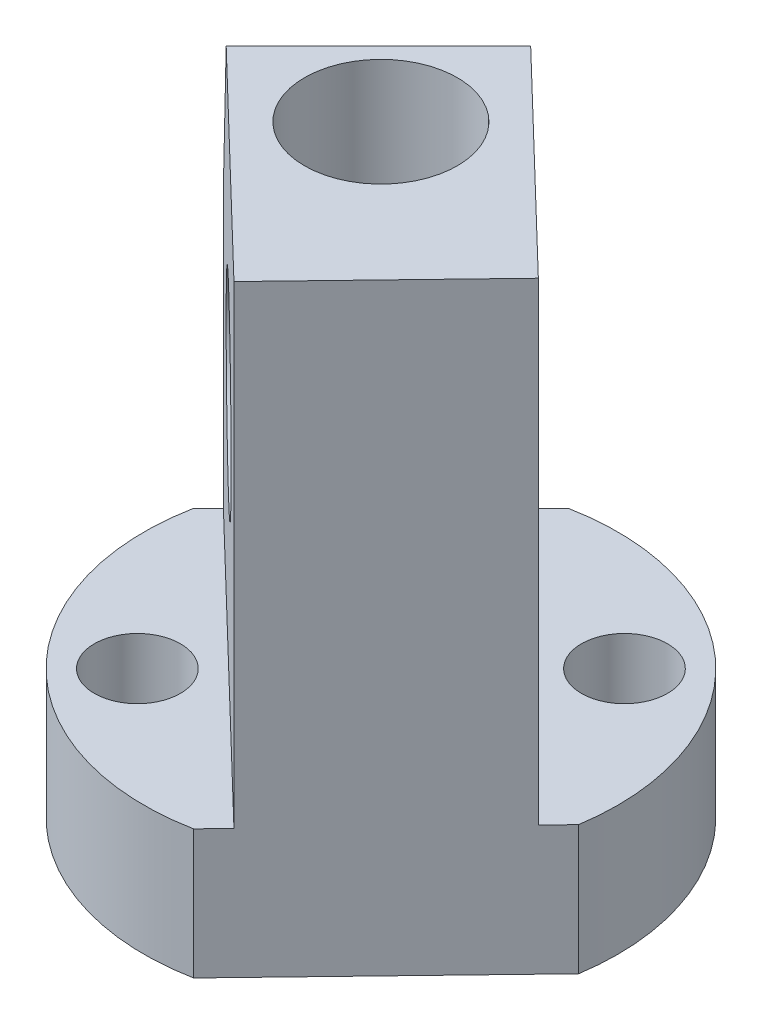
SolidWorks part; units mm, degrees
ref_plane "Plan de face" through (0, 0, 0) normal (0, 0, 1) x (1, 0, 0)
ref_plane "Plan de dessus" through (0, 0, 0) normal (0, 1, 0) x (1, 0, 0)
ref_plane "Plan de droite" through (0, 0, 0) normal (1, 0, 0) x (0, 0, -1)
ref_plane "Plan1" through (0, 0, 0) normal (0, 0, -1) x (-1, 0, 0)
sketch "Esquisse1" plane through (0, 0, 0) normal (0, 0, -1) x (-1, 0, 0)
  line L0 (-11, 0) -> (0, 0)
  line L1 (0, 0) -> (0, 6)
  line L2 (0, 6) -> (-11, 6)
  line L3 (-11, 6) -> (-11, 0)
  line L4 (0, 0) -> (0, 6) construction
revolve "Révolution1" add sketch "Esquisse1" angle 360 about L4
sketch "Esquisse2" plane through (0, 6, 0) normal (0, 1, 0) x (-1, 0, 0)
  line L0 (-9.9516, 2.6394) -> (-3.0164, 9.8438)
  line L1 (-3.0164, 9.8438) -> (10.0888, -2.7715)
  line L2 (10.0888, -2.7715) -> (3.0164, -9.8438)
  line L3 (3.0164, -9.8438) -> (-9.9516, 2.6394)
extrude "Boss.-Extru.1" add sketch "Esquisse2" along normal blind 22
hole_wizard "Diamètre du perçage Ø7.1 (7.1)1" positions "Esquisse4" profile "Esquisse3" hole size "Ø7.1" standard "Ansi Metric"
sketch "Esquisse4" plane through (0, 28, 0) normal (0, 1, 0) x (1, 0, 0)
  point P0 (0, 0)
sketch "Esquisse3" plane through (0, 28, 0) normal (1, 0, 0) x (0, 0, 1)
  line L0 (0, 0) -> (0, 6)
  line L1 (0, 6) -> (3.55, 6)
  line L2 (3.55, 6) -> (3.55, 0)
  line L5 (3.55, 0) -> (0, 0)
  line L10 (0, 6) -> (-3.55, 6) construction
  line L11 (0, -6.35) -> (0, 107.95) construction
  dimension "Diamètre du perçage" = 7.1
  dimension "Profondeur du perçage" = 6
  dimension "Angle de pointe" = 180
hole_wizard "Diamètre du perçage Ø8.5 (8.5)1" positions "Esquisse6" profile "Esquisse5" hole size "Ø8.5" standard "Ansi Metric" end condition through all
sketch "Esquisse6" plane through (-3.4676, 0, 3.6022) normal (-0.6935, 0, 0.7204) x (0.7204, 0, 0.6935)
  point P0 (-0.1905, 17)
sketch "Esquisse5" plane through (-3.6048, 17, 3.4701) normal (0, 1, 0) x (0.7204, 0, 0.6935)
  line L0 (0, 0) -> (0, 20.5535)
  line L1 (0, 20.5535) -> (4.25, 20.5535)
  line L2 (4.25, 20.5535) -> (4.25, 0)
  line L5 (4.25, 0) -> (0, 0)
  line L11 (0, -6.35) -> (0, 107.95) construction
  dimension "Diamètre du perçage jusqu'au prochain" = 8.5
  dimension "Profondeur du perçage jusqu'au prochain" = 20.5535
hole_wizard "Chambrage pour vis à tête hexagonale M21" positions "Esquisse8" profile "Esquisse7" counterbore size "M2" standard "Ansi Metric"
sketch "Esquisse8" plane through (0, 6, 0) normal (0, 1, 0) x (1, 0, 0)
  point P0 (5.6569, 5.6569)
  point P1 (-5.6569, -5.6569)
sketch "Esquisse7" plane through (5.6569, 6, -5.6569) normal (1, 0, 0) x (0, 0, 1)
  line L0 (0, 0) -> (0, 6)
  line L1 (0, 6) -> (1.25, 6)
  line L3 (1.25, 6) -> (1.25, 4.5)
  line L4 (1.25, 4.5) -> (2, 4.5)
  line L5 (2, 4.5) -> (2, 0)
  line L7 (2, 0) -> (0, 0)
  line L11 (0, -6.35) -> (0, 107.95) construction
  dimension "Diamètre du perçage jusqu'au prochain" = 2.5
  dimension "Profondeur du perçage jusqu'au prochain" = 6
  dimension "Diamètre du chambrage" = 4
  dimension "Profondeur du chambrage" = 4.5
hole_wizard "Diamètre du perçage Ø8.0 (8)1" positions "Esquisse10" profile "Esquisse9" hole size "Ø8.0" standard "Ansi Metric"
sketch "Esquisse10" plane through (0, 0, 0) normal (0, -1, 0) x (-1, 0, 0)
  point P0 (0, 0)
sketch "Esquisse9" plane through (0, 0, 0) normal (1, 0, 0) x (0, 0, -1)
  line L0 (0, 0) -> (0, 6)
  line L1 (0, 6) -> (4, 2)
  line L2 (4, 2) -> (4, 0)
  line L5 (4, 0) -> (0, 0)
  line L10 (0, 6) -> (-4, 2) construction
  line L11 (0, -6.35) -> (0, 107.95) construction
  dimension "Diamètre du perçage" = 8
  dimension "Profondeur du perçage" = 2
  dimension "Angle de pointe" = 90
chamfer "Chanfrein1" distance 9 angle 28 1 edges at (-6.5526, 28, -6.3077)
sketch "Esquisse11" plane through (0, 6, 0) normal (0, 1, 0) x (1, 0, 0)
  line L0 (1.2043, -11.7264) -> (11.6206, -0.9056)
  line L1 (0.5456, 13.4058) -> (-12.4779, 0.3823)
  line L2 (1.2043, -11.7264) -> (5.1296, -15.5049)
  line L3 (5.1296, -15.5049) -> (15.5459, -4.6841)
  line L4 (15.5459, -4.6841) -> (11.6206, -0.9056)
  line L6 (-12.4779, 0.3823) -> (-16.04, 3.9443)
  line L7 (-16.04, 3.9443) -> (-3.0164, 16.9679)
  line L8 (-3.0164, 16.9679) -> (0.5456, 13.4058)
extrude "Enlèv. mat.-Extru.1" cut sketch "Esquisse11" against normal blind 10
